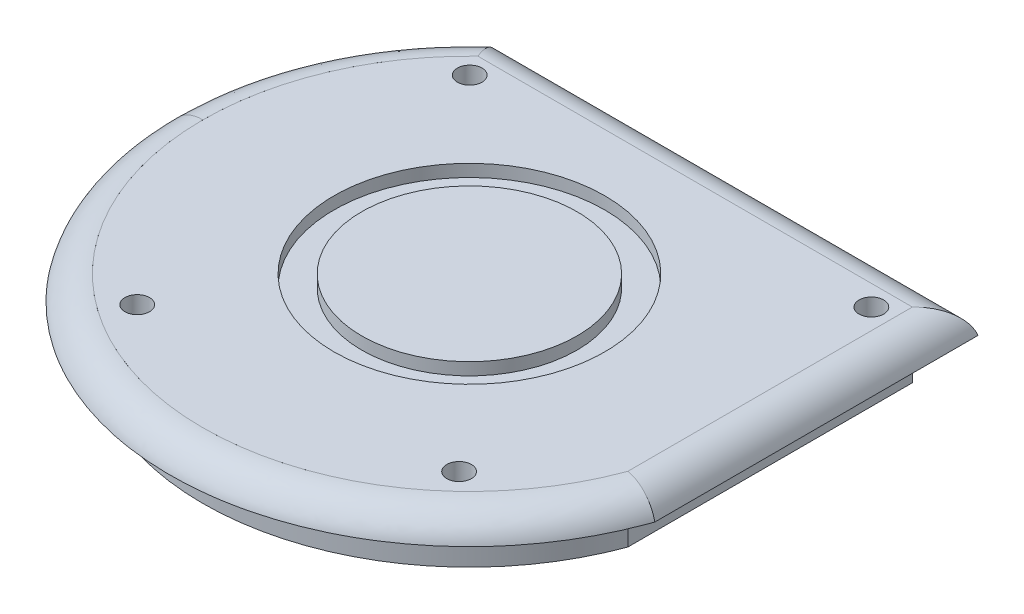
SolidWorks part; units mm, degrees
ref_plane "前视基准面" through (0, 0, 0) normal (0, 0, 1) x (1, 0, 0)
ref_plane "上视基准面" through (0, 0, 0) normal (0, 1, 0) x (1, 0, 0)
ref_plane "右视基准面" through (0, 0, 0) normal (1, 0, 0) x (0, 0, -1)
sketch "Sketch1" plane through (0, 0, 0) normal (0, 1, 0) x (1, 0, 0)
  line L0 (61.02, 46.9907) -> (-44.9096, 46.9907)
  line L1 (61.02, 60.8664) -> (61.02, -22.3955) construction
  line L3 (61.02, -22.3955) -> (61.02, 46.9907)
  line L4 (61.02, -40.4005) -> (61.02, -65.6046) construction
  line L5 (76.1327, 47) -> (113.2479, 47) construction
  arc A1 (-44.9096, 46.9907) -> (61.02, -22.3955) centre (0, 0) ccw
  dimension "D3" = 61.02
extrude "Boss-Extrude1" add sketch "Sketch1" along normal blind 1
sketch "Sketch2" plane through (0, 1, 0) normal (0, 1, 0) x (1, 0, 0)
  line L0 (61.02, 46.9907) -> (-44.9096, 46.9907) construction
  line L1 (61.02, -22.3955) -> (61.02, 46.9907) construction
  circle A0 centre (-41.9096, 41.9907) radius 3
  circle A1 centre (56.02, 41.9907) radius 3
  circle A2 centre (40.5, -43.0093) radius 3
  circle A3 centre (-33.98, -47.0093) radius 3
  dimension "D1" = 6
  dimension "D4" = 5
  dimension "D6" = 20.52
  dimension "D7" = 90
  dimension "D8" = 94
  dimension "D9" = 95
  dimension "D10" = 6
  dimension "D11" = 6
  dimension "D12" = 6
  dimension "D2" = 5
  dimension "D3" = 3
  dimension "D5" = 5
extrude "Cut-Extrude1" cut sketch "Sketch2" against normal up to next
sketch "Sketch3" plane through (0, 0, 0) normal (0, -1, 0) x (1, 0, 0)
  circle A0 centre (56.02, -41.9907) radius 3
  circle A1 centre (56.02, -41.9907) radius 4
  circle A2 centre (-41.9096, -41.9907) radius 3
  circle A3 centre (-41.9096, -41.9907) radius 4
  circle A4 centre (40.5, 43.0093) radius 3
  circle A5 centre (40.5, 43.0093) radius 4
  circle A6 centre (-33.98, 47.0093) radius 3
  circle A7 centre (-33.98, 47.0093) radius 4
extrude "Boss-Extrude2" add sketch "Sketch3" along normal blind 15
sketch "Sketch4" plane through (0, -15, 0) normal (0, -1, 0) x (1, 0, 0)
  circle A0 centre (56.02, -41.9907) radius 3
  circle A1 centre (56.02, -41.9907) radius 1.5
  circle A2 centre (-41.9096, -41.9907) radius 3
  circle A3 centre (-41.9096, -41.9907) radius 1.5
  circle A4 centre (-33.98, 47.0093) radius 3
  circle A5 centre (-33.98, 47.0093) radius 1.5
  circle A6 centre (40.5, 43.0093) radius 3
  circle A7 centre (40.5, 43.0093) radius 1.5
extrude "Boss-Extrude3" add sketch "Sketch4" against normal blind 2
sketch "Sketch5" plane through (0, 0, 0) normal (0, -1, 0) x (1, 0, 0)
  line L2 (61.02, -46.9907) -> (-44.9096, -46.9907) construction
  line L3 (61.02, 22.3955) -> (61.02, -46.9907) construction
  line L4 (-43.6901, -43.9907) -> (58.02, -43.9907)
  line L5 (58.02, -43.9907) -> (58.02, 21.8559)
  line L6 (-38.4455, -43.9907) -> (52.5559, -43.9907)
  line L7 (58.02, -38.5266) -> (58.02, 21.8559)
  line L8 (61.02, -46.9907) -> (-44.9096, -46.9907)
  line L9 (61.02, 22.3955) -> (61.02, -46.9907)
  arc A0 (40.4251, 47.0086) -> (-36.1623, 50.3616) centre (0, 0) ccw
  circle A1 centre (-33.98, 47.0093) radius 4 construction
  arc A2 (58.02, 21.8559) -> (-43.6901, -43.9907) centre (0, 0) ccw
  arc A3 (58.02, 21.8559) -> (44.4966, 43.1747) centre (0, 0) ccw
  circle A4 centre (40.5, 43.0093) radius 4 construction
  circle A5 centre (56.02, -41.9907) radius 4 construction
  circle A6 centre (-41.9096, -41.9907) radius 4 construction
  arc A7 (61.02, 22.3955) -> (-44.9096, -46.9907) centre (0, 0) ccw construction
  arc A8 (-36.1623, 50.3616) -> (-36.4787, 50.1329) centre (-33.98, 47.0093) ccw
  arc A9 (44.4966, 43.1747) -> (40.4251, 47.0086) centre (40.5, 43.0093) ccw
  arc A10 (52.5559, -43.9907) -> (58.02, -38.5266) centre (56.02, -41.9907) ccw
  arc A11 (-45.8977, -41.6821) -> (-38.4455, -43.9907) centre (-41.9096, -41.9907) ccw
  arc A12 (61.02, 22.3955) -> (-44.9096, -46.9907) centre (0, 0) ccw
  arc A13 (-36.4787, 50.1329) -> (-45.8977, -41.6821) centre (0, 0) ccw
  dimension "D1" = 3
extrude "Boss-Extrude4" add sketch "Sketch5" along normal blind 15
ref_plane "Plane1" through (0, -5, 0) normal (0, -1, 0) x (-1, 0, 0)
sketch "Sketch6" plane through (0, -5, 0) normal (0, -1, 0) x (-1, 0, 0)
  line L0 (-61.02, -22.3955) -> (-61.02, 46.9907) construction
  line L1 (-61.02, 46.9907) -> (44.9096, 46.9907) construction
  line L2 (-61.02, -22.3955) -> (-61.02, 46.9907)
  line L3 (-61.02, 46.9907) -> (44.9096, 46.9907)
  line L4 (-69.02, 54.9907) -> (48.0107, 54.9907)
  line L5 (-69.02, -23.7748) -> (-69.02, 54.9907)
  arc A0 (-61.02, -22.3955) -> (44.9096, 46.9907) centre (0, 0) ccw construction
  arc A1 (-61.02, -22.3955) -> (44.9096, 46.9907) centre (0, 0) ccw
  arc A2 (-69.02, -23.7748) -> (48.0107, 54.9907) centre (0, 0) ccw
  dimension "D1" = 8
sketch "Sketch7" plane through (0, 0, 0) normal (0, 0, 1) x (1, 0, 0)
  line L1 (-73, -5) -> (69.02, -5) construction
  line L2 (-73, -5) -> (-65, -5)
  line L3 (-65, 1) -> (-65, -15) construction
  line L4 (-65, -5) -> (-65, 1)
  arc A0 (-65, 1) -> (-73, -5) centre (-65.2256, -7.0325) ccw
surface "Surface-Sweep1"
sketch "Sketch8" plane through (0, 0, 0) normal (0, 1, 0) x (1, 0, 0)
  circle A0 centre (0, 0) radius 33
  circle A1 centre (0, 0) radius 26.25
  circle A2 centre (0, 0) radius 25
  circle A3 centre (0, 0) radius 34
extrude "Boss-Extrude5" add sketch "Sketch8" against normal blind 3 contours A3 A0 | A1 A2
sketch "Sketch9" plane through (0, -3, 0) normal (0, -1, 0) x (1, 0, 0)
  circle A0 centre (0, 0) radius 34
extrude "Boss-Extrude6" add sketch "Sketch9" against normal blind 1
sketch "Sketch10" plane through (0, 1, 0) normal (0, 1, 0) x (1, 0, 0)
  circle A2 centre (0, 0) radius 26.25
  circle A3 centre (0, 0) radius 33
extrude "Cut-Extrude6" cut sketch "Sketch10" against normal blind 1
